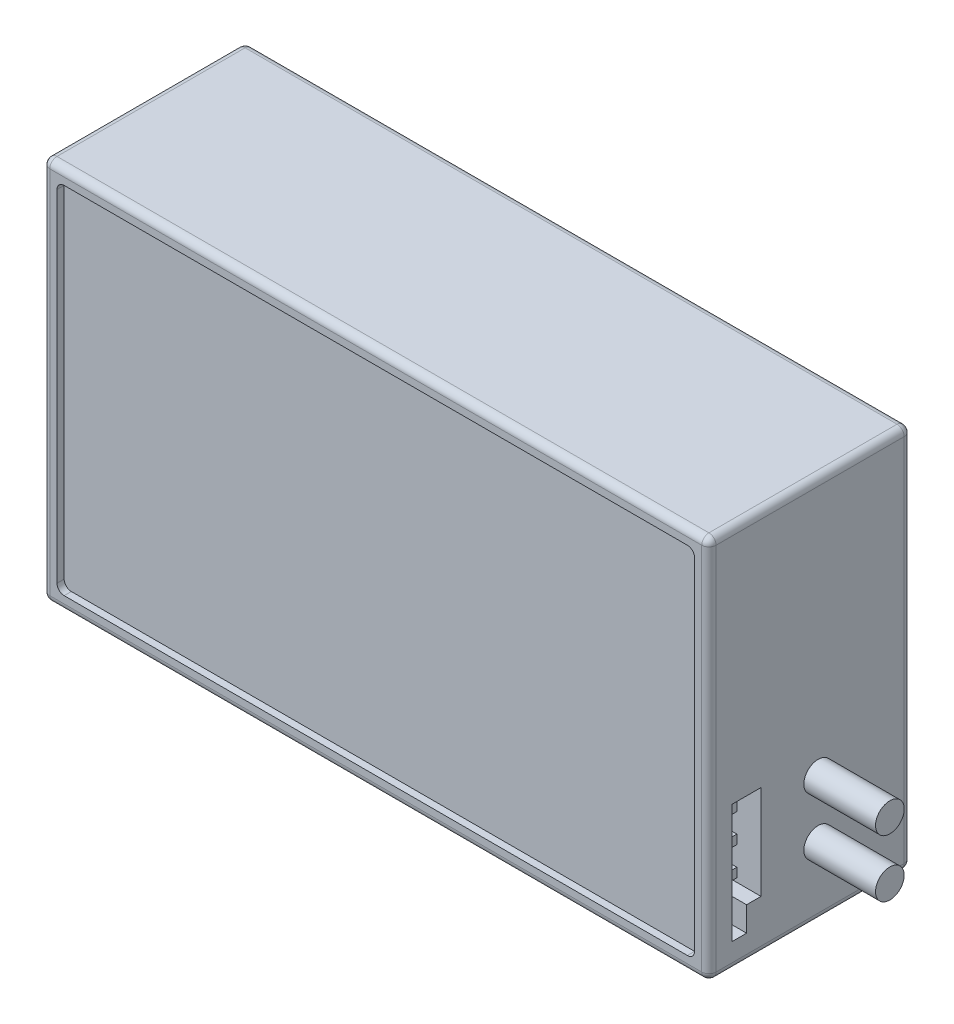
SolidWorks part; units mm, degrees
ref_plane "Front Plane" through (0, 0, 0) normal (0, 0, 1) x (1, 0, 0)
ref_plane "Top Plane" through (0, 0, 0) normal (0, 1, 0) x (1, 0, 0)
ref_plane "Right Plane" through (0, 0, 0) normal (1, 0, 0) x (0, 0, -1)
sketch "Sketch3" plane through (0, 0, 0) normal (0, 0, 1) x (1, 0, 0)
  line L1 (23.235, -13.39) -> (-23.235, -13.39)
  line L2 (23.235, -13.39) -> (23.235, 13.39)
  line L3 (23.235, 13.39) -> (-23.235, 13.39)
  line L4 (-23.235, -13.39) -> (-23.235, 13.39)
  line L5 (23.235, -13.39) -> (-23.235, 13.39) construction
  line L6 (23.235, 13.39) -> (-23.235, -13.39) construction
  point P0 (0, 0)
  dimension "D1" = 46.47
  dimension "D2" = 26.78
extrude "Boss-Extrude1" add sketch "Sketch3" along normal blind 14.12
sketch "Sketch4" plane through (0, 0, 14.12) normal (0, 0, 1) x (1, 0, 0)
  line L12 (-22.235, 12.39) -> (-22.235, -12.39)
  line L13 (-22.235, -12.39) -> (22.235, -12.39)
  line L14 (22.235, -12.39) -> (22.235, 12.39)
  line L15 (22.235, 12.39) -> (-22.235, 12.39)
  line L16 (-22.235, 12.39) -> (-22.235, -12.39)
  line L17 (-22.235, -12.39) -> (22.235, -12.39)
  line L18 (22.235, -12.39) -> (22.235, 12.39)
  line L19 (22.235, 12.39) -> (-22.235, 12.39)
  dimension "D1" = 1
extrude "Cut-Extrude1" cut sketch "Sketch4" against normal blind 0.5
fillet "Fillet1" radius 0.5 4 edges at (22.235, -12.39, 13.87) (-22.235, -12.39, 13.87) (22.235, 12.39, 13.87) (-22.235, 12.39, 13.87)
fillet "Fillet2" radius 0.5 12 edges at (-23.235, 0, 14.12) (-23.235, -13.39, 7.06) (0, -13.39, 14.12) (0, 13.39, 14.12) (-23.235, 13.39, 7.06) (23.235, -13.39, 7.06) (23.235, 0, 14.12) (23.235, 13.39, 7.06) (0, -13.39, 0) (23.235, 0, 0) (0, 13.39, 0) (-23.235, 0, 0)
sketch "Sketch5" plane through (-23.235, 0, 0) normal (-1, 0, 0) x (0, 0, 1)
  line L12 (1.5, -11.89) -> (12.62, -11.89)
  line L13 (12.62, -11.89) -> (12.62, 11.89)
  line L14 (12.62, 11.89) -> (1.5, 11.89)
  line L15 (1.5, 11.89) -> (1.5, -11.89)
  line L16 (1.5, -11.89) -> (12.62, -11.89)
  line L17 (12.62, -11.89) -> (12.62, 11.89)
  line L18 (12.62, 11.89) -> (1.5, 11.89)
  line L19 (1.5, 11.89) -> (1.5, -11.89)
  dimension "D1" = 1
extrude "Cut-Extrude2" cut sketch "Sketch5" against normal blind 8
sketch "Sketch6" plane through (-15.235, 0, 0) normal (-1, 0, 0) x (0, 0, 1)
  line L0 (12.62, -11.89) -> (12.62, 11.89) construction
  line L1 (11.87, 11.89) -> (10.37, 11.89)
  line L2 (12.12, 11.64) -> (12.12, 7.14)
  line L3 (11.87, 6.89) -> (10.37, 6.89)
  line L4 (10.12, 11.64) -> (10.12, 7.14)
  line L17 (4.8309, 11.89) -> (4.8309, -11.89) construction
  line L18 (12.62, 11.89) -> (1.5, 11.89) construction
  line L20 (1.5, -11.89) -> (12.62, -11.89) construction
  line L23 (9.37, 11.89) -> (7.87, 11.89)
  line L24 (9.62, 11.64) -> (9.62, 7.14)
  line L25 (9.37, 6.89) -> (7.87, 6.89)
  line L26 (7.62, 11.64) -> (7.62, 7.14)
  line L28 (6.87, 11.89) -> (5.37, 11.89)
  line L29 (7.12, 11.64) -> (7.12, 7.14)
  line L30 (6.87, 6.89) -> (5.37, 6.89)
  line L31 (5.12, 11.64) -> (5.12, 7.14)
  arc A0 (5.37, 11.89) -> (5.12, 11.64) centre (5.37, 11.64) ccw
  arc A1 (5.37, 6.89) -> (5.12, 7.14) centre (5.37, 7.14) cw
  arc A2 (7.12, 7.14) -> (6.87, 6.89) centre (6.87, 7.14) cw
  arc A3 (6.87, 11.89) -> (7.12, 11.64) centre (6.87, 11.64) cw
  arc A4 (7.87, 11.89) -> (7.62, 11.64) centre (7.87, 11.64) ccw
  arc A5 (7.87, 6.89) -> (7.62, 7.14) centre (7.87, 7.14) cw
  arc A6 (9.62, 7.14) -> (9.37, 6.89) centre (9.37, 7.14) cw
  arc A7 (9.37, 11.89) -> (9.62, 11.64) centre (9.37, 11.64) cw
  arc A8 (10.37, 11.89) -> (10.12, 11.64) centre (10.37, 11.64) ccw
  arc A9 (12.12, 7.14) -> (11.87, 6.89) centre (11.87, 7.14) cw
  arc A10 (10.37, 6.89) -> (10.12, 7.14) centre (10.37, 7.14) cw
  arc A11 (11.87, 11.89) -> (12.12, 11.64) centre (11.87, 11.64) cw
  point P40 (12.12, 6.89)
  point P43 (10.12, 6.89)
  point P46 (12.12, 11.89)
  dimension "D8" = 0.25
  dimension "D1" = 5
  dimension "D2" = 0
  dimension "D3" = 0
  dimension "D4" = 2
  dimension "D5" = 0.5
  dimension "0" = 0
  dimension "D6" = 0.5
  dimension "D7" = 0.5
extrude "Boss-Extrude2" add sketch "Sketch6" along normal blind 0.5
pattern_linear "LPattern1" count 4 spacing 6.2 along (0, -1, 0) of "Boss-Extrude2"
sketch "Sketch7" plane through (-15.735, 0, 0) normal (-1, 0, 0) x (0, 0, 1)
  line L0 (11.12, 11.89) -> (11.12, 6.89) construction
  line L1 (11.87, 11.89) -> (10.37, 11.89) construction
  line L2 (10.37, 6.89) -> (11.87, 6.89) construction
  line L3 (10.37, 6.89) -> (11.87, 6.89) construction
  line L4 (10.8, 10.64) -> (11.44, 10.64)
  line L5 (10.8, 10.64) -> (10.8, 10)
  line L6 (10.8, 10) -> (11.44, 10)
  line L7 (11.44, 10.64) -> (11.44, 10)
  line L8 (10.8, 10.64) -> (11.44, 10) construction
  line L9 (10.8, 10) -> (11.44, 10.64) construction
  line L10 (10.8, 8.78) -> (11.44, 8.78)
  line L11 (10.8, 8.78) -> (10.8, 8.14)
  line L12 (10.8, 8.14) -> (11.44, 8.14)
  line L13 (11.44, 8.78) -> (11.44, 8.14)
  line L14 (10.8, 8.78) -> (11.44, 8.14) construction
  line L15 (10.8, 8.14) -> (11.44, 8.78) construction
  line L16 (8.62, 6.89) -> (8.62, 11.89) construction
  line L17 (7.87, 6.89) -> (9.37, 6.89) construction
  line L18 (9.37, 11.89) -> (7.87, 11.89) construction
  point P6 (11.12, 10.32)
  point P11 (11.12, 8.46)
  dimension "D1" = 5
  dimension "D2" = 1.25
  dimension "D3" = 0.64
  dimension "D4" = 0.64
  dimension "D5" = 1.25
  dimension "D6" = 2.5
extrude "Boss-Extrude3" add sketch "Sketch7" along normal blind 5
pattern_linear "LPattern2" count 3 spacing 2.5 along (0, 0, -1) of "Boss-Extrude3"
pattern_linear "LPattern3" count 4 spacing 6.2 along (0, -1, 0) of "Boss-Extrude3", "LPattern2"
sketch "Sketch8" plane through (-23.235, 0, 0) normal (-1, 0, 0) x (0, 0, 1)
  line L1 (12.42, 9.7244) -> (13.3477, 9.7244)
  line L2 (12.42, 9.7244) -> (12.42, 9.0556)
  line L3 (12.42, 9.0556) -> (13.3477, 9.0556)
  line L4 (13.3477, 9.7244) -> (13.3477, 9.0556)
  line L5 (12.42, 9.7244) -> (13.3477, 9.0556) construction
  line L6 (12.42, 9.0556) -> (13.3477, 9.7244) construction
  line L7 (10.8, 10.64) -> (10.8, 10) construction
  line L8 (10.8, 8.78) -> (10.8, 8.14) construction
  line L9 (11.44, 8.14) -> (11.44, 8.78) construction
  line L10 (11.44, 10) -> (11.44, 10.64) construction
  line L11 (12.62, -11.89) -> (12.62, 11.89) construction
  point P0 (12.8838, 9.39)
  point P9 (10.8, 10.32)
  point P12 (10.8, 8.46)
  point P13 (11.44, 8.46)
  point P16 (11.44, 10.32)
  dimension "D1" = 1.86
  dimension "D2" = 0.93
  dimension "D3" = 0.2
  dimension "D4" = 0.93
extrude "Cut-Extrude4" cut sketch "Sketch8" against normal up to surface (8 mm away) up to face at (-15.235, 8.0486, 8.3971)
pattern_linear "LPattern4" count 7 spacing 3.1 along (0, -1, 0) of "Cut-Extrude4"
sketch "Sketch9" plane through (23.235, 0, 0) normal (1, 0, 0) x (0, 0, -1)
  line L0 (-12.502, -11.6063) -> (-12.502, -3.3125)
  line L1 (-12.502, -3.3125) -> (-10.4846, -3.3125)
  line L2 (-10.4846, -3.3125) -> (-10.4846, -9.8878)
  line L3 (-10.4846, -9.8878) -> (-11.4933, -9.8878)
  line L4 (-11.4933, -9.8878) -> (-11.4933, -11.6063)
  line L5 (-11.4933, -11.6063) -> (-12.502, -11.6063)
extrude "Cut-Extrude5" cut sketch "Sketch9" against normal blind 6
sketch "Sketch11" plane through (17.235, 0, 0) normal (1, 0, 0) x (0, 0, -1)
  line L0 (-11.4933, -9.8878) -> (-11.4933, -3.3125) construction
  line L1 (-10.4846, -3.3125) -> (-12.502, -3.3125) construction
  line L3 (-11.1733, -6.9202) -> (-11.8133, -6.9202)
  line L4 (-11.1733, -6.9202) -> (-11.1733, -6.2802)
  line L5 (-11.1733, -6.2802) -> (-11.8133, -6.2802)
  line L6 (-11.8133, -6.9202) -> (-11.8133, -6.2802)
  line L7 (-11.1733, -6.9202) -> (-11.8133, -6.2802) construction
  line L8 (-11.1733, -6.2802) -> (-11.8133, -6.9202) construction
  point P5 (-11.4933, -6.6002)
  dimension "D1" = 0.64
  dimension "D2" = 0.64
extrude "Boss-Extrude4" add sketch "Sketch11" along normal blind 5
pattern_linear "LPattern5" count 2 spacing 2 along (0, 1, 0) of "Boss-Extrude4"
pattern_linear "LPattern6" count 2 spacing 2 along (0, -1, 0) of "LPattern5"
sketch "Sketch12" plane through (23.235, 0, 0) normal (1, 0, 0) x (0, 0, -1)
  line L0 (-11.1733, -8.6002) -> (-2.1659, -8.6002) construction
  line L1 (-11.1733, -8.9202) -> (-11.1733, -8.2802) construction
  line L2 (-11.1733, -4.6002) -> (-1.9169, -4.6002) construction
  line L3 (-11.1733, -4.9202) -> (-11.1733, -4.2802) construction
  line L4 (-0.5, -12.89) -> (-0.5, 12.89) construction
  circle A0 centre (-6.5, -8.6002) radius 1
  circle A1 centre (-6.5, -4.6002) radius 1
  dimension "D1" = 2
  dimension "D2" = 6
  dimension "D3" = 6
extrude "Boss-Extrude5" add sketch "Sketch12" along normal blind 5
sketch "Sketch13" plane through (-15.235, 0, 0) normal (-1, 0, 0) x (0, 0, 1)
  line L0 (4.7064, 11.89) -> (4.7064, -11.89)
  line L1 (5.37, 11.89) -> (1.5, 11.89) construction
  line L2 (1.5, -11.89) -> (12.62, -11.89) construction
  line L3 (4.7064, -11.89) -> (4.1833, -11.89)
  line L4 (1.5, -11.89) -> (12.62, -11.89) construction
  line L5 (4.1833, -11.89) -> (4.1833, -0.6227)
  line L6 (4.1833, -0.6227) -> (3.1622, -0.6227)
  line L7 (3.1622, -0.6227) -> (3.1622, -1.4197)
  line L8 (3.1622, -1.4197) -> (1.5, -1.4197)
  line L9 (1.5, 11.89) -> (1.5, -11.89) construction
  line L10 (1.5, -1.4197) -> (1.5, 2.8144)
  line L11 (1.5, 2.8144) -> (2.3311, 2.8144)
  line L12 (2.3311, 2.8144) -> (2.3311, 3.4869)
  line L13 (2.3311, 3.4869) -> (4.1833, 3.4869)
  line L14 (4.1833, 3.4869) -> (4.1833, 11.89)
  line L15 (4.1833, 11.89) -> (4.7064, 11.89)
extrude "Boss-Extrude6" add sketch "Sketch13" along normal up to surface (8 mm away) up to face at (-23.235, 0.0787, 12.2434)
sketch "Sketch15" plane through (-15.235, 0, 0) normal (-1, 0, 0) x (0, 0, 1)
  line L0 (5.8, 10.32) -> (2.1908, 10.32) construction
  line L1 (5.8, 10.64) -> (5.8, 10) construction
  line L4 (2.3311, 3.4869) -> (2.3311, 11.89) construction
  line L9 (2.5217, 8.0084) -> (3.1617, 8.0084)
  line L10 (2.5217, 8.0084) -> (2.5217, 7.3684)
  line L11 (4.1833, 11.89) -> (1.5, 11.89) construction
  line L12 (2.8417, 11.89) -> (2.8417, 10.32) construction
  line L13 (4.1833, 11.89) -> (1.5, 11.89) construction
  line L14 (4.1833, 3.4869) -> (2.3311, 3.4869) construction
  line L15 (4.1833, 7.6884) -> (1.5, 7.6884) construction
  line L16 (4.1833, 3.4869) -> (4.1833, 11.89) construction
  line L17 (1.5, 11.89) -> (1.5, 2.8144) construction
  line L18 (2.3311, 8.46) -> (2.1908, 8.46) construction
  line L19 (2.8417, 8.14) -> (2.8417, 3.4869) construction
  line L20 (2.5217, 7.3684) -> (3.1617, 7.3684)
  line L21 (3.1617, 8.0084) -> (3.1617, 7.3684)
  line L22 (2.5217, 8.0084) -> (3.1617, 7.3684) construction
  line L23 (2.5217, 7.3684) -> (3.1617, 8.0084) construction
  point P6 (2.8417, 7.6884)
  point P8 (2.8417, 8.46)
  dimension "D1" = 0.64
  dimension ".64" = 0.64
extrude "Boss-Extrude7" add sketch "Sketch15" along normal blind 5
pattern_linear "LPattern8" count 2 spacing 2.5 along (0, -1, 0) of "Boss-Extrude7"
pattern_linear "LPattern9" count 2 spacing 2.5 along (0, 1, 0) of "Boss-Extrude7"
sketch "Sketch16" plane through (-15.235, 0, 0) normal (-1, 0, 0) x (0, 0, 1)
  line L0 (1.5, -6.6548) -> (4.1833, -6.6548) construction
  line L1 (1.5, -1.4197) -> (1.5, -11.89) construction
  line L2 (4.1833, -0.6227) -> (4.1833, -11.89) construction
  line L3 (2.8417, -11.89) -> (2.8417, -1.4197) construction
  line L4 (1.5, -11.89) -> (4.1833, -11.89) construction
  line L5 (1.5, -1.4197) -> (3.1622, -1.4197) construction
  line L7 (2.5217, -6.3348) -> (3.1617, -6.3348)
  line L8 (2.5217, -6.3348) -> (2.5217, -6.9748)
  line L9 (2.5217, -6.9748) -> (3.1617, -6.9748)
  line L10 (3.1617, -6.3348) -> (3.1617, -6.9748)
  line L11 (2.5217, -6.3348) -> (3.1617, -6.9748) construction
  line L12 (2.5217, -6.9748) -> (3.1617, -6.3348) construction
  point P12 (2.8417, -6.6548)
  dimension "D1" = 0.64
  dimension "D2" = 0.64
extrude "Boss-Extrude8" add sketch "Sketch16" along normal blind 5
pattern_linear "LPattern10" count 2 spacing 2.5 along (0, -1, 0) of "Boss-Extrude8"
pattern_linear "LPattern11" count 2 spacing 2.5 along (0, 1, 0) of "Boss-Extrude8"
